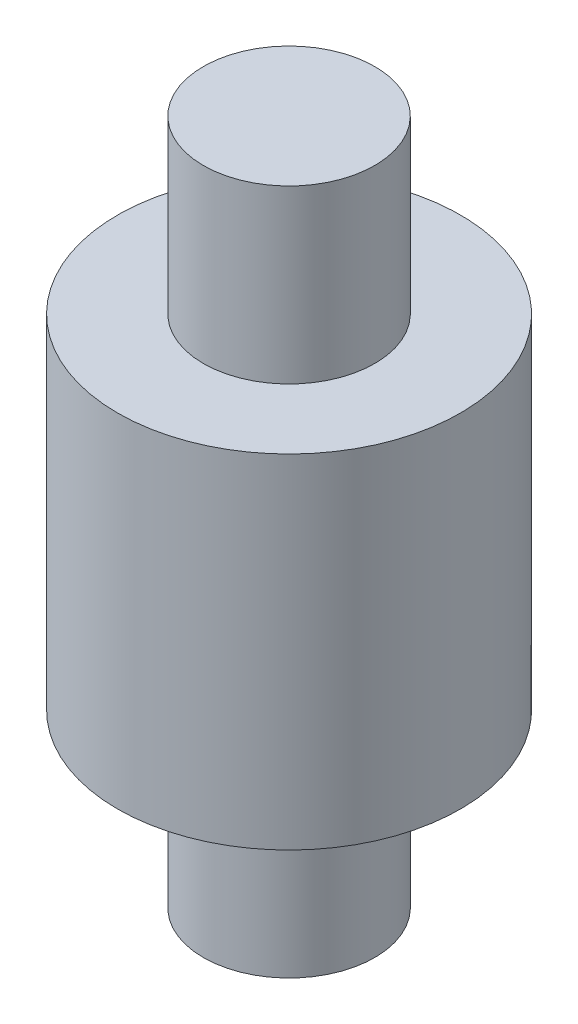
SolidWorks part; units mm, degrees
ref_plane "前视基准面" through (0, 0, 0) normal (0, 0, 1) x (1, 0, 0)
ref_plane "上视基准面" through (0, 0, 0) normal (0, 1, 0) x (1, 0, 0)
ref_plane "右视基准面" through (0, 0, 0) normal (1, 0, 0) x (0, 0, -1)
other "Configuration Table"
sketch "草图1" plane through (0, 0, 0) normal (0, 1, 0) x (1, 0, 0)
  circle A0 centre (0, 0) radius 1
  dimension "D1" = 2
extrude "凸台-拉伸1" add sketch "草图1" along normal blind 2
sketch "草图2" plane through (0, 2, 0) normal (0, 1, 0) x (1, 0, 0)
  circle A0 centre (0, 0) radius 2
  dimension "D1" = 4
extrude "凸台-拉伸2" add sketch "草图2" along normal blind 4
sketch "草图3" plane through (0, 6, 0) normal (0, 1, 0) x (1, 0, 0)
  circle A0 centre (0, 0) radius 1
  dimension "D1" = 2
extrude "凸台-拉伸3" add sketch "草图3" along normal blind 2
